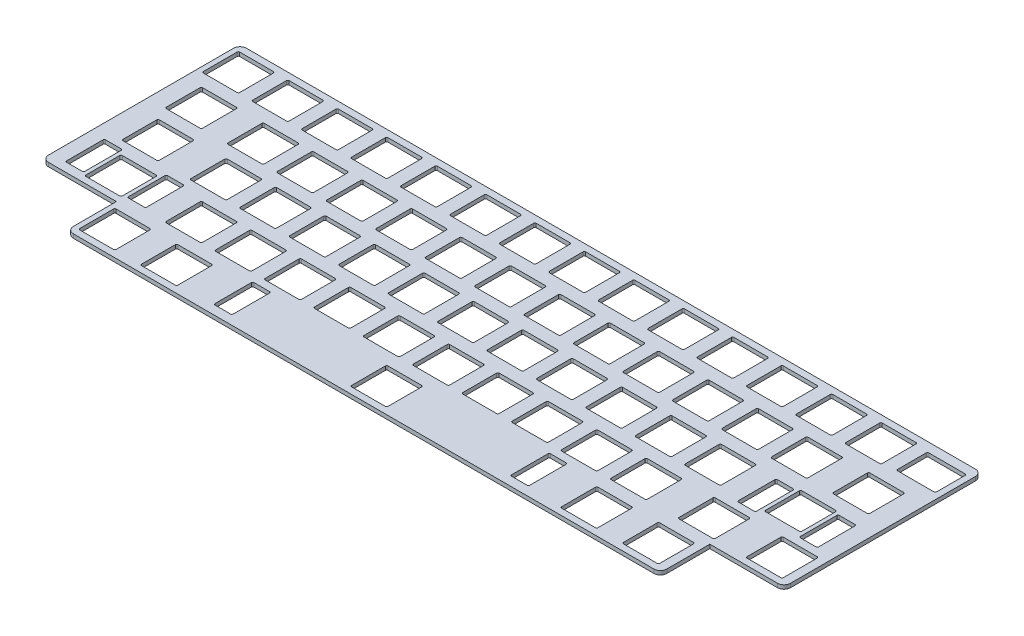
SolidWorks part; units mm, degrees
ref_plane "Front Plane" through (0, 0, 0) normal (0, 0, 1) x (1, 0, 0)
ref_plane "Top Plane" through (0, 0, 0) normal (0, 1, 0) x (1, 0, 0)
ref_plane "Right Plane" through (0, 0, 0) normal (1, 0, 0) x (0, 0, -1)
sketch "Sketch1" plane through (0, 0, 0) normal (0, 1, 0) x (1, 0, 0)
  line L0 (3.0233, -2.5236) -> (16.0159, -2.5236)
  line L1 (3.0233, -16.5156) -> (16.0159, -16.5156)
  line L2 (2.5236, -3.0233) -> (2.5236, -16.0159)
  line L3 (16.5156, -3.0233) -> (16.5156, -16.0159)
  line L4 (22.0624, -2.5236) -> (35.055, -2.5236)
  line L5 (22.0624, -16.5156) -> (35.055, -16.5156)
  line L6 (21.5627, -3.0233) -> (21.5627, -16.0159)
  line L7 (35.5547, -3.0233) -> (35.5547, -16.0159)
  line L8 (41.1015, -2.5236) -> (54.0941, -2.5236)
  line L9 (41.1015, -16.5156) -> (54.0941, -16.5156)
  line L10 (40.6018, -3.0233) -> (40.6018, -16.0159)
  line L11 (54.5938, -3.0233) -> (54.5938, -16.0159)
  line L12 (60.1407, -2.5236) -> (73.1333, -2.5236)
  line L13 (60.1407, -16.5156) -> (73.1333, -16.5156)
  line L14 (59.641, -3.0233) -> (59.641, -16.0159)
  line L15 (73.633, -3.0233) -> (73.633, -16.0159)
  line L16 (79.1798, -2.5236) -> (92.1724, -2.5236)
  line L17 (79.1798, -16.5156) -> (92.1724, -16.5156)
  line L18 (78.6801, -3.0233) -> (78.6801, -16.0159)
  line L19 (92.6721, -3.0233) -> (92.6721, -16.0159)
  line L20 (98.2189, -2.5236) -> (111.2115, -2.5236)
  line L21 (98.2189, -16.5156) -> (111.2115, -16.5156)
  line L22 (97.7192, -3.0233) -> (97.7192, -16.0159)
  line L23 (111.7112, -3.0233) -> (111.7112, -16.0159)
  line L24 (117.2581, -2.5236) -> (130.2506, -2.5236)
  line L25 (117.2581, -16.5156) -> (130.2506, -16.5156)
  line L26 (116.7584, -3.0233) -> (116.7584, -16.0159)
  line L27 (130.7504, -3.0233) -> (130.7504, -16.0159)
  line L28 (136.2972, -2.5236) -> (149.2898, -2.5236)
  line L29 (136.2972, -16.5156) -> (149.2898, -16.5156)
  line L30 (135.7975, -3.0233) -> (135.7975, -16.0159)
  line L31 (149.7895, -3.0233) -> (149.7895, -16.0159)
  line L32 (155.3363, -2.5236) -> (168.3289, -2.5236)
  line L33 (155.3363, -16.5156) -> (168.3289, -16.5156)
  line L34 (154.8366, -3.0233) -> (154.8366, -16.0159)
  line L35 (168.8286, -3.0233) -> (168.8286, -16.0159)
  line L36 (174.3755, -2.5236) -> (187.368, -2.5236)
  line L37 (174.3755, -16.5156) -> (187.368, -16.5156)
  line L38 (173.8757, -3.0233) -> (173.8757, -16.0159)
  line L39 (187.8678, -3.0233) -> (187.8678, -16.0159)
  line L40 (193.4146, -2.5236) -> (206.4072, -2.5236)
  line L41 (193.4146, -16.5156) -> (206.4072, -16.5156)
  line L42 (192.9149, -3.0233) -> (192.9149, -16.0159)
  line L43 (206.9069, -3.0233) -> (206.9069, -16.0159)
  line L44 (212.4537, -2.5236) -> (225.4463, -2.5236)
  line L45 (212.4537, -16.5156) -> (225.4463, -16.5156)
  line L46 (211.954, -3.0233) -> (211.954, -16.0159)
  line L47 (225.946, -3.0233) -> (225.946, -16.0159)
  line L48 (231.4929, -2.5236) -> (244.4854, -2.5236)
  line L49 (231.4929, -16.5156) -> (244.4854, -16.5156)
  line L50 (230.9931, -3.0233) -> (230.9931, -16.0159)
  line L51 (244.9852, -3.0233) -> (244.9852, -16.0159)
  line L52 (250.532, -2.5236) -> (263.5246, -2.5236)
  line L53 (250.532, -16.5156) -> (263.5246, -16.5156)
  line L54 (250.0323, -3.0233) -> (250.0323, -16.0159)
  line L55 (264.0243, -3.0233) -> (264.0243, -16.0159)
  line L56 (7.7831, -21.5627) -> (20.7756, -21.5627)
  line L57 (7.7831, -35.5547) -> (20.7756, -35.5547)
  line L58 (7.2833, -22.0624) -> (7.2833, -35.055)
  line L59 (21.2754, -22.0624) -> (21.2754, -35.055)
  line L60 (31.582, -21.5627) -> (44.5746, -21.5627)
  line L61 (31.582, -35.5547) -> (44.5746, -35.5547)
  line L62 (31.0823, -22.0624) -> (31.0823, -35.055)
  line L63 (45.0743, -22.0624) -> (45.0743, -35.055)
  line L64 (50.6211, -21.5627) -> (63.6137, -21.5627)
  line L65 (50.6211, -35.5547) -> (63.6137, -35.5547)
  line L66 (50.1214, -22.0624) -> (50.1214, -35.055)
  line L67 (64.1134, -22.0624) -> (64.1134, -35.055)
  line L68 (69.6602, -21.5627) -> (82.6528, -21.5627)
  line L69 (69.6602, -35.5547) -> (82.6528, -35.5547)
  line L70 (69.1605, -22.0624) -> (69.1605, -35.055)
  line L71 (83.1525, -22.0624) -> (83.1525, -35.055)
  line L72 (88.6994, -21.5627) -> (101.692, -21.5627)
  line L73 (88.6994, -35.5547) -> (101.692, -35.5547)
  line L74 (88.1997, -22.0624) -> (88.1997, -35.055)
  line L75 (102.1917, -22.0624) -> (102.1917, -35.055)
  line L76 (107.7385, -21.5627) -> (120.7311, -21.5627)
  line L77 (107.7385, -35.5547) -> (120.7311, -35.5547)
  line L78 (107.2388, -22.0624) -> (107.2388, -35.055)
  line L79 (121.2308, -22.0624) -> (121.2308, -35.055)
  line L80 (126.7776, -21.5627) -> (139.7702, -21.5627)
  line L81 (126.7776, -35.5547) -> (139.7702, -35.5547)
  line L82 (126.2779, -22.0624) -> (126.2779, -35.055)
  line L83 (140.2699, -22.0624) -> (140.2699, -35.055)
  line L84 (145.8168, -21.5627) -> (158.8093, -21.5627)
  line L85 (145.8168, -35.5547) -> (158.8093, -35.5547)
  line L86 (145.317, -22.0624) -> (145.317, -35.055)
  line L87 (159.3091, -22.0624) -> (159.3091, -35.055)
  line L88 (164.8559, -21.5627) -> (177.8485, -21.5627)
  line L89 (164.8559, -35.5547) -> (177.8485, -35.5547)
  line L90 (164.3562, -22.0624) -> (164.3562, -35.055)
  line L91 (178.3482, -22.0624) -> (178.3482, -35.055)
  line L92 (183.895, -21.5627) -> (196.8876, -21.5627)
  line L93 (183.895, -35.5547) -> (196.8876, -35.5547)
  line L94 (183.3953, -22.0624) -> (183.3953, -35.055)
  line L95 (197.3873, -22.0624) -> (197.3873, -35.055)
  line L96 (202.9342, -21.5627) -> (215.9267, -21.5627)
  line L97 (202.9342, -35.5547) -> (215.9267, -35.5547)
  line L98 (202.4344, -22.0624) -> (202.4344, -35.055)
  line L99 (216.4265, -22.0624) -> (216.4265, -35.055)
  line L100 (221.9733, -21.5627) -> (234.9659, -21.5627)
  line L101 (221.9733, -35.5547) -> (234.9659, -35.5547)
  line L102 (221.4736, -22.0624) -> (221.4736, -35.055)
  line L103 (235.4656, -22.0624) -> (235.4656, -35.055)
  line L104 (241.0124, -21.5627) -> (254.005, -21.5627)
  line L105 (241.0124, -35.5547) -> (254.005, -35.5547)
  line L106 (240.5127, -22.0624) -> (240.5127, -35.055)
  line L107 (254.5047, -22.0624) -> (254.5047, -35.055)
  line L108 (264.8113, -21.5627) -> (277.8039, -21.5627)
  line L109 (264.8113, -35.5547) -> (277.8039, -35.5547)
  line L110 (264.3116, -22.0624) -> (264.3116, -35.055)
  line L111 (278.3036, -22.0624) -> (278.3036, -35.055)
  line L112 (10.1629, -40.6018) -> (23.1555, -40.6018)
  line L113 (10.1629, -54.5938) -> (23.1555, -54.5938)
  line L114 (9.6632, -41.1015) -> (9.6632, -54.0941)
  line L115 (23.6552, -41.1015) -> (23.6552, -54.0941)
  line L116 (36.3418, -40.6018) -> (49.3343, -40.6018)
  line L117 (36.3418, -54.5938) -> (49.3343, -54.5938)
  line L118 (35.842, -41.1015) -> (35.842, -54.0941)
  line L119 (49.8341, -41.1015) -> (49.8341, -54.0941)
  line L120 (55.3809, -40.6018) -> (68.3735, -40.6018)
  line L121 (55.3809, -54.5938) -> (68.3735, -54.5938)
  line L122 (54.8812, -41.1015) -> (54.8812, -54.0941)
  line L123 (68.8732, -41.1015) -> (68.8732, -54.0941)
  line L124 (74.42, -40.6018) -> (87.4126, -40.6018)
  line L125 (74.42, -54.5938) -> (87.4126, -54.5938)
  line L126 (73.9203, -41.1015) -> (73.9203, -54.0941)
  line L127 (87.9123, -41.1015) -> (87.9123, -54.0941)
  line L128 (93.4592, -40.6018) -> (106.4517, -40.6018)
  line L129 (93.4592, -54.5938) -> (106.4517, -54.5938)
  line L130 (92.9594, -41.1015) -> (92.9594, -54.0941)
  line L131 (106.9514, -41.1015) -> (106.9514, -54.0941)
  line L132 (112.4983, -40.6018) -> (125.4909, -40.6018)
  line L133 (112.4983, -54.5938) -> (125.4909, -54.5938)
  line L134 (111.9986, -41.1015) -> (111.9986, -54.0941)
  line L135 (125.9906, -41.1015) -> (125.9906, -54.0941)
  line L136 (131.5374, -40.6018) -> (144.53, -40.6018)
  line L137 (131.5374, -54.5938) -> (144.53, -54.5938)
  line L138 (131.0377, -41.1015) -> (131.0377, -54.0941)
  line L139 (145.0297, -41.1015) -> (145.0297, -54.0941)
  line L140 (150.5765, -40.6018) -> (163.5691, -40.6018)
  line L141 (150.5765, -54.5938) -> (163.5691, -54.5938)
  line L142 (150.0768, -41.1015) -> (150.0768, -54.0941)
  line L143 (164.0688, -41.1015) -> (164.0688, -54.0941)
  line L144 (169.6157, -40.6018) -> (182.6083, -40.6018)
  line L145 (169.6157, -54.5938) -> (182.6083, -54.5938)
  line L146 (169.116, -41.1015) -> (169.116, -54.0941)
  line L147 (183.108, -41.1015) -> (183.108, -54.0941)
  line L148 (188.6548, -40.6018) -> (201.6474, -40.6018)
  line L149 (188.6548, -54.5938) -> (201.6474, -54.5938)
  line L150 (188.1551, -41.1015) -> (188.1551, -54.0941)
  line L151 (202.1471, -41.1015) -> (202.1471, -54.0941)
  line L152 (207.6939, -40.6018) -> (220.6865, -40.6018)
  line L153 (207.6939, -54.5938) -> (220.6865, -54.5938)
  line L154 (207.1942, -41.1015) -> (207.1942, -54.0941)
  line L155 (221.1862, -41.1015) -> (221.1862, -54.0941)
  line L156 (226.7331, -40.6018) -> (239.7257, -40.6018)
  line L157 (226.7331, -54.5938) -> (239.7257, -54.5938)
  line L158 (226.2334, -41.1015) -> (226.2334, -54.0941)
  line L159 (240.2254, -41.1015) -> (240.2254, -54.0941)
  line L160 (257.6717, -40.6018) -> (270.6642, -40.6018)
  line L161 (257.6717, -54.5938) -> (270.6642, -54.5938)
  line L162 (257.172, -41.1015) -> (257.172, -54.0941)
  line L163 (271.164, -41.1015) -> (271.164, -54.0941)
  line L164 (249.2385, -41.6013) -> (255.2351, -41.6013)
  line L165 (249.2385, -56.5927) -> (255.2351, -56.5927)
  line L166 (248.7388, -42.101) -> (248.7388, -56.093)
  line L167 (255.7348, -42.101) -> (255.7348, -56.093)
  line L168 (273.1009, -41.6013) -> (279.0974, -41.6013)
  line L169 (273.1009, -56.5927) -> (279.0974, -56.5927)
  line L170 (272.6011, -42.101) -> (272.6011, -56.093)
  line L171 (279.5971, -42.101) -> (279.5971, -56.093)
  line L172 (45.8613, -59.641) -> (58.8539, -59.641)
  line L173 (45.8613, -73.633) -> (58.8539, -73.633)
  line L174 (45.3616, -60.1407) -> (45.3616, -73.1333)
  line L175 (59.3536, -60.1407) -> (59.3536, -73.1333)
  line L176 (64.9005, -59.641) -> (77.893, -59.641)
  line L177 (64.9005, -73.633) -> (77.893, -73.633)
  line L178 (64.4007, -60.1407) -> (64.4007, -73.1333)
  line L179 (78.3928, -60.1407) -> (78.3928, -73.1333)
  line L180 (83.9396, -59.641) -> (96.9322, -59.641)
  line L181 (83.9396, -73.633) -> (96.9322, -73.633)
  line L182 (83.4399, -60.1407) -> (83.4399, -73.1333)
  line L183 (97.4319, -60.1407) -> (97.4319, -73.1333)
  line L184 (102.9787, -59.641) -> (115.9713, -59.641)
  line L185 (102.9787, -73.633) -> (115.9713, -73.633)
  line L186 (102.479, -60.1407) -> (102.479, -73.1333)
  line L187 (116.471, -60.1407) -> (116.471, -73.1333)
  line L188 (122.0178, -59.641) -> (135.0104, -59.641)
  line L189 (122.0178, -73.633) -> (135.0104, -73.633)
  line L190 (121.5181, -60.1407) -> (121.5181, -73.1333)
  line L191 (135.5101, -60.1407) -> (135.5101, -73.1333)
  line L192 (141.057, -59.641) -> (154.0496, -59.641)
  line L193 (141.057, -73.633) -> (154.0496, -73.633)
  line L194 (140.5573, -60.1407) -> (140.5573, -73.1333)
  line L195 (154.5493, -60.1407) -> (154.5493, -73.1333)
  line L196 (160.0961, -59.641) -> (173.0887, -59.641)
  line L197 (160.0961, -73.633) -> (173.0887, -73.633)
  line L198 (159.5964, -60.1407) -> (159.5964, -73.1333)
  line L199 (173.5884, -60.1407) -> (173.5884, -73.1333)
  line L200 (179.1352, -59.641) -> (192.1278, -59.641)
  line L201 (179.1352, -73.633) -> (192.1278, -73.633)
  line L202 (178.6355, -60.1407) -> (178.6355, -73.1333)
  line L203 (192.6275, -60.1407) -> (192.6275, -73.1333)
  line L204 (198.1744, -59.641) -> (211.167, -59.641)
  line L205 (198.1744, -73.633) -> (211.167, -73.633)
  line L206 (197.6747, -60.1407) -> (197.6747, -73.1333)
  line L207 (211.6667, -60.1407) -> (211.6667, -73.1333)
  line L208 (217.2135, -59.641) -> (230.2061, -59.641)
  line L209 (217.2135, -73.633) -> (230.2061, -73.633)
  line L210 (216.7138, -60.1407) -> (216.7138, -73.1333)
  line L211 (230.7058, -60.1407) -> (230.7058, -73.1333)
  line L212 (243.3923, -59.641) -> (256.3849, -59.641)
  line L213 (243.3923, -73.633) -> (256.3849, -73.633)
  line L214 (242.8926, -60.1407) -> (242.8926, -73.1333)
  line L215 (256.8846, -60.1407) -> (256.8846, -73.1333)
  line L216 (269.5711, -59.641) -> (282.5637, -59.641)
  line L217 (269.5711, -73.633) -> (282.5637, -73.633)
  line L218 (269.0714, -60.1407) -> (269.0714, -73.1333)
  line L219 (283.0634, -60.1407) -> (283.0634, -73.1333)
  line L220 (31.582, -78.6801) -> (44.5746, -78.6801)
  line L221 (31.582, -92.6721) -> (44.5746, -92.6721)
  line L222 (31.0823, -79.1798) -> (31.0823, -92.1724)
  line L223 (45.0743, -79.1798) -> (45.0743, -92.1724)
  line L224 (55.3809, -78.6801) -> (68.3735, -78.6801)
  line L225 (55.3809, -92.6721) -> (68.3735, -92.6721)
  line L226 (54.8812, -79.1798) -> (54.8812, -92.1724)
  line L227 (68.8732, -79.1798) -> (68.8732, -92.1724)
  line L228 (217.2135, -78.6801) -> (230.2061, -78.6801)
  line L229 (217.2135, -92.6721) -> (230.2061, -92.6721)
  line L230 (216.7138, -79.1798) -> (216.7138, -92.1724)
  line L231 (230.7058, -79.1798) -> (230.7058, -92.1724)
  line L232 (241.0124, -78.6801) -> (254.005, -78.6801)
  line L233 (241.0124, -92.6721) -> (254.005, -92.6721)
  line L234 (240.5127, -79.1798) -> (240.5127, -92.1724)
  line L235 (254.5047, -79.1798) -> (254.5047, -92.1724)
  line L236 (27.9153, -73.633) -> (14.9227, -73.633)
  line L237 (27.9153, -59.641) -> (14.9227, -59.641)
  line L238 (28.415, -73.1333) -> (28.415, -60.1407)
  line L239 (14.423, -73.1333) -> (14.423, -60.1407)
  line L240 (36.3485, -72.6335) -> (30.3519, -72.6335)
  line L241 (36.3485, -57.6421) -> (30.3519, -57.6421)
  line L242 (36.8482, -72.1338) -> (36.8482, -58.1418)
  line L243 (29.8522, -72.1338) -> (29.8522, -58.1418)
  line L244 (12.4861, -72.6335) -> (6.4895, -72.6335)
  line L245 (12.4861, -57.6421) -> (6.4895, -57.6421)
  line L246 (12.9858, -72.1338) -> (12.9858, -58.1418)
  line L247 (5.9898, -72.1338) -> (5.9898, -58.1418)
  line L248 (149.2898, -92.6721) -> (136.2972, -92.6721)
  line L249 (149.2898, -78.6801) -> (136.2972, -78.6801)
  line L250 (149.7895, -92.1724) -> (149.7895, -79.1798)
  line L251 (135.7975, -92.1724) -> (135.7975, -79.1798)
  line L252 (202.9092, -91.6727) -> (196.9126, -91.6727)
  line L253 (202.9092, -76.6812) -> (196.9126, -76.6812)
  line L254 (203.4089, -91.173) -> (203.4089, -77.1809)
  line L255 (196.4129, -91.173) -> (196.4129, -77.1809)
  line L256 (88.6744, -91.6727) -> (82.6778, -91.6727)
  line L257 (88.6744, -76.6812) -> (82.6778, -76.6812)
  line L258 (89.1741, -91.173) -> (89.1741, -77.1809)
  line L259 (82.1781, -91.173) -> (82.1781, -77.1809)
  line L260 (0.5696, -95.1957) -> (286.3196, -95.1957) construction
  line L261 (0.5696, 0.0543) -> (286.3196, 0.0543)
  line L262 (0.5696, -95.1957) -> (0.5696, 0.0543) construction
  line L263 (286.3196, -95.1957) -> (286.3196, 0.0543) construction
  line L264 (29.1446, -95.1957) -> (29.1446, -76.1457)
  line L265 (29.1446, -76.1457) -> (0.5696, -76.1457)
  line L266 (0.5696, 0.0543) -> (0.5696, -76.1457)
  line L267 (286.3196, -76.1457) -> (257.7446, -76.1457)
  line L268 (257.7446, -76.1457) -> (257.7446, -95.1957)
  line L269 (29.1446, -95.1957) -> (257.7446, -95.1957)
  line L270 (286.3196, 0.0543) -> (286.3196, -76.1457)
  line L271 (264.0243, -9.5196) -> (266.6022, -9.5196) construction
  line L272 (266.6022, -9.5196) -> (286.3196, -9.5196) construction
  line L279 (257.0283, -2.5236) -> (257.0283, 0.0543) construction
  line L280 (276.4609, -15.5196) -> (276.4609, -3.5196) construction
  line L281 (283.4609, -3.5196) -> (269.4609, -3.5196)
  line L282 (268.9609, -4.0196) -> (268.9609, -15.0196)
  line L283 (269.4609, -15.5196) -> (283.4609, -15.5196)
  line L284 (283.9609, -15.0196) -> (283.9609, -4.0196)
  arc A0 (3.0233, -2.5236) -> (2.5236, -3.0233) centre (3.0233, -3.0233) ccw
  arc A1 (16.5156, -3.0233) -> (16.0159, -2.5236) centre (16.0159, -3.0233) ccw
  arc A2 (2.5236, -16.0159) -> (3.0233, -16.5156) centre (3.0233, -16.0159) ccw
  arc A3 (16.0159, -16.5156) -> (16.5156, -16.0159) centre (16.0159, -16.0159) ccw
  arc A4 (22.0624, -2.5236) -> (21.5627, -3.0233) centre (22.0624, -3.0233) ccw
  arc A5 (35.5547, -3.0233) -> (35.055, -2.5236) centre (35.055, -3.0233) ccw
  arc A6 (21.5627, -16.0159) -> (22.0624, -16.5156) centre (22.0624, -16.0159) ccw
  arc A7 (35.055, -16.5156) -> (35.5547, -16.0159) centre (35.055, -16.0159) ccw
  arc A8 (41.1015, -2.5236) -> (40.6018, -3.0233) centre (41.1015, -3.0233) ccw
  arc A9 (54.5938, -3.0233) -> (54.0941, -2.5236) centre (54.0941, -3.0233) ccw
  arc A10 (40.6018, -16.0159) -> (41.1015, -16.5156) centre (41.1015, -16.0159) ccw
  arc A11 (54.0941, -16.5156) -> (54.5938, -16.0159) centre (54.0941, -16.0159) ccw
  arc A12 (60.1407, -2.5236) -> (59.641, -3.0233) centre (60.1407, -3.0233) ccw
  arc A13 (73.633, -3.0233) -> (73.1333, -2.5236) centre (73.1333, -3.0233) ccw
  arc A14 (59.641, -16.0159) -> (60.1407, -16.5156) centre (60.1407, -16.0159) ccw
  arc A15 (73.1333, -16.5156) -> (73.633, -16.0159) centre (73.1333, -16.0159) ccw
  arc A16 (79.1798, -2.5236) -> (78.6801, -3.0233) centre (79.1798, -3.0233) ccw
  arc A17 (92.6721, -3.0233) -> (92.1724, -2.5236) centre (92.1724, -3.0233) ccw
  arc A18 (78.6801, -16.0159) -> (79.1798, -16.5156) centre (79.1798, -16.0159) ccw
  arc A19 (92.1724, -16.5156) -> (92.6721, -16.0159) centre (92.1724, -16.0159) ccw
  arc A20 (98.2189, -2.5236) -> (97.7192, -3.0233) centre (98.2189, -3.0233) ccw
  arc A21 (111.7112, -3.0233) -> (111.2115, -2.5236) centre (111.2115, -3.0233) ccw
  arc A22 (97.7192, -16.0159) -> (98.2189, -16.5156) centre (98.2189, -16.0159) ccw
  arc A23 (111.2115, -16.5156) -> (111.7112, -16.0159) centre (111.2115, -16.0159) ccw
  arc A24 (117.2581, -2.5236) -> (116.7584, -3.0233) centre (117.2581, -3.0233) ccw
  arc A25 (130.7504, -3.0233) -> (130.2506, -2.5236) centre (130.2506, -3.0233) ccw
  arc A26 (116.7584, -16.0159) -> (117.2581, -16.5156) centre (117.2581, -16.0159) ccw
  arc A27 (130.2506, -16.5156) -> (130.7504, -16.0159) centre (130.2506, -16.0159) ccw
  arc A28 (136.2972, -2.5236) -> (135.7975, -3.0233) centre (136.2972, -3.0233) ccw
  arc A29 (149.7895, -3.0233) -> (149.2898, -2.5236) centre (149.2898, -3.0233) ccw
  arc A30 (135.7975, -16.0159) -> (136.2972, -16.5156) centre (136.2972, -16.0159) ccw
  arc A31 (149.2898, -16.5156) -> (149.7895, -16.0159) centre (149.2898, -16.0159) ccw
  arc A32 (155.3363, -2.5236) -> (154.8366, -3.0233) centre (155.3363, -3.0233) ccw
  arc A33 (168.8286, -3.0233) -> (168.3289, -2.5236) centre (168.3289, -3.0233) ccw
  arc A34 (154.8366, -16.0159) -> (155.3363, -16.5156) centre (155.3363, -16.0159) ccw
  arc A35 (168.3289, -16.5156) -> (168.8286, -16.0159) centre (168.3289, -16.0159) ccw
  arc A36 (174.3755, -2.5236) -> (173.8757, -3.0233) centre (174.3755, -3.0233) ccw
  arc A37 (187.8678, -3.0233) -> (187.368, -2.5236) centre (187.368, -3.0233) ccw
  arc A38 (173.8757, -16.0159) -> (174.3755, -16.5156) centre (174.3755, -16.0159) ccw
  arc A39 (187.368, -16.5156) -> (187.8678, -16.0159) centre (187.368, -16.0159) ccw
  arc A40 (193.4146, -2.5236) -> (192.9149, -3.0233) centre (193.4146, -3.0233) ccw
  arc A41 (206.9069, -3.0233) -> (206.4072, -2.5236) centre (206.4072, -3.0233) ccw
  arc A42 (192.9149, -16.0159) -> (193.4146, -16.5156) centre (193.4146, -16.0159) ccw
  arc A43 (206.4072, -16.5156) -> (206.9069, -16.0159) centre (206.4072, -16.0159) ccw
  arc A44 (212.4537, -2.5236) -> (211.954, -3.0233) centre (212.4537, -3.0233) ccw
  arc A45 (225.946, -3.0233) -> (225.4463, -2.5236) centre (225.4463, -3.0233) ccw
  arc A46 (211.954, -16.0159) -> (212.4537, -16.5156) centre (212.4537, -16.0159) ccw
  arc A47 (225.4463, -16.5156) -> (225.946, -16.0159) centre (225.4463, -16.0159) ccw
  arc A48 (231.4929, -2.5236) -> (230.9931, -3.0233) centre (231.4929, -3.0233) ccw
  arc A49 (244.9852, -3.0233) -> (244.4854, -2.5236) centre (244.4854, -3.0233) ccw
  arc A50 (230.9931, -16.0159) -> (231.4929, -16.5156) centre (231.4929, -16.0159) ccw
  arc A51 (244.4854, -16.5156) -> (244.9852, -16.0159) centre (244.4854, -16.0159) ccw
  arc A52 (250.532, -2.5236) -> (250.0323, -3.0233) centre (250.532, -3.0233) ccw
  arc A53 (264.0243, -3.0233) -> (263.5246, -2.5236) centre (263.5246, -3.0233) ccw
  arc A54 (250.0323, -16.0159) -> (250.532, -16.5156) centre (250.532, -16.0159) ccw
  arc A55 (263.5246, -16.5156) -> (264.0243, -16.0159) centre (263.5246, -16.0159) ccw
  arc A56 (7.7831, -21.5627) -> (7.2833, -22.0624) centre (7.7831, -22.0624) ccw
  arc A57 (21.2754, -22.0624) -> (20.7756, -21.5627) centre (20.7756, -22.0624) ccw
  arc A58 (7.2833, -35.055) -> (7.7831, -35.5547) centre (7.7831, -35.055) ccw
  arc A59 (20.7756, -35.5547) -> (21.2754, -35.055) centre (20.7756, -35.055) ccw
  arc A60 (31.582, -21.5627) -> (31.0823, -22.0624) centre (31.582, -22.0624) ccw
  arc A61 (45.0743, -22.0624) -> (44.5746, -21.5627) centre (44.5746, -22.0624) ccw
  arc A62 (31.0823, -35.055) -> (31.582, -35.5547) centre (31.582, -35.055) ccw
  arc A63 (44.5746, -35.5547) -> (45.0743, -35.055) centre (44.5746, -35.055) ccw
  arc A64 (50.6211, -21.5627) -> (50.1214, -22.0624) centre (50.6211, -22.0624) ccw
  arc A65 (64.1134, -22.0624) -> (63.6137, -21.5627) centre (63.6137, -22.0624) ccw
  arc A66 (50.1214, -35.055) -> (50.6211, -35.5547) centre (50.6211, -35.055) ccw
  arc A67 (63.6137, -35.5547) -> (64.1134, -35.055) centre (63.6137, -35.055) ccw
  arc A68 (69.6602, -21.5627) -> (69.1605, -22.0624) centre (69.6602, -22.0624) ccw
  arc A69 (83.1525, -22.0624) -> (82.6528, -21.5627) centre (82.6528, -22.0624) ccw
  arc A70 (69.1605, -35.055) -> (69.6602, -35.5547) centre (69.6602, -35.055) ccw
  arc A71 (82.6528, -35.5547) -> (83.1525, -35.055) centre (82.6528, -35.055) ccw
  arc A72 (88.6994, -21.5627) -> (88.1997, -22.0624) centre (88.6994, -22.0624) ccw
  arc A73 (102.1917, -22.0624) -> (101.692, -21.5627) centre (101.692, -22.0624) ccw
  arc A74 (88.1997, -35.055) -> (88.6994, -35.5547) centre (88.6994, -35.055) ccw
  arc A75 (101.692, -35.5547) -> (102.1917, -35.055) centre (101.692, -35.055) ccw
  arc A76 (107.7385, -21.5627) -> (107.2388, -22.0624) centre (107.7385, -22.0624) ccw
  arc A77 (121.2308, -22.0624) -> (120.7311, -21.5627) centre (120.7311, -22.0624) ccw
  arc A78 (107.2388, -35.055) -> (107.7385, -35.5547) centre (107.7385, -35.055) ccw
  arc A79 (120.7311, -35.5547) -> (121.2308, -35.055) centre (120.7311, -35.055) ccw
  arc A80 (126.7776, -21.5627) -> (126.2779, -22.0624) centre (126.7776, -22.0624) ccw
  arc A81 (140.2699, -22.0624) -> (139.7702, -21.5627) centre (139.7702, -22.0624) ccw
  arc A82 (126.2779, -35.055) -> (126.7776, -35.5547) centre (126.7776, -35.055) ccw
  arc A83 (139.7702, -35.5547) -> (140.2699, -35.055) centre (139.7702, -35.055) ccw
  arc A84 (145.8168, -21.5627) -> (145.317, -22.0624) centre (145.8168, -22.0624) ccw
  arc A85 (159.3091, -22.0624) -> (158.8093, -21.5627) centre (158.8093, -22.0624) ccw
  arc A86 (145.317, -35.055) -> (145.8168, -35.5547) centre (145.8168, -35.055) ccw
  arc A87 (158.8093, -35.5547) -> (159.3091, -35.055) centre (158.8093, -35.055) ccw
  arc A88 (164.8559, -21.5627) -> (164.3562, -22.0624) centre (164.8559, -22.0624) ccw
  arc A89 (178.3482, -22.0624) -> (177.8485, -21.5627) centre (177.8485, -22.0624) ccw
  arc A90 (164.3562, -35.055) -> (164.8559, -35.5547) centre (164.8559, -35.055) ccw
  arc A91 (177.8485, -35.5547) -> (178.3482, -35.055) centre (177.8485, -35.055) ccw
  arc A92 (183.895, -21.5627) -> (183.3953, -22.0624) centre (183.895, -22.0624) ccw
  arc A93 (197.3873, -22.0624) -> (196.8876, -21.5627) centre (196.8876, -22.0624) ccw
  arc A94 (183.3953, -35.055) -> (183.895, -35.5547) centre (183.895, -35.055) ccw
  arc A95 (196.8876, -35.5547) -> (197.3873, -35.055) centre (196.8876, -35.055) ccw
  arc A96 (202.9342, -21.5627) -> (202.4344, -22.0624) centre (202.9342, -22.0624) ccw
  arc A97 (216.4265, -22.0624) -> (215.9267, -21.5627) centre (215.9267, -22.0624) ccw
  arc A98 (202.4344, -35.055) -> (202.9342, -35.5547) centre (202.9342, -35.055) ccw
  arc A99 (215.9267, -35.5547) -> (216.4265, -35.055) centre (215.9267, -35.055) ccw
  arc A100 (221.9733, -21.5627) -> (221.4736, -22.0624) centre (221.9733, -22.0624) ccw
  arc A101 (235.4656, -22.0624) -> (234.9659, -21.5627) centre (234.9659, -22.0624) ccw
  arc A102 (221.4736, -35.055) -> (221.9733, -35.5547) centre (221.9733, -35.055) ccw
  arc A103 (234.9659, -35.5547) -> (235.4656, -35.055) centre (234.9659, -35.055) ccw
  arc A104 (241.0124, -21.5627) -> (240.5127, -22.0624) centre (241.0124, -22.0624) ccw
  arc A105 (254.5047, -22.0624) -> (254.005, -21.5627) centre (254.005, -22.0624) ccw
  arc A106 (240.5127, -35.055) -> (241.0124, -35.5547) centre (241.0124, -35.055) ccw
  arc A107 (254.005, -35.5547) -> (254.5047, -35.055) centre (254.005, -35.055) ccw
  arc A108 (264.8113, -21.5627) -> (264.3116, -22.0624) centre (264.8113, -22.0624) ccw
  arc A109 (278.3036, -22.0624) -> (277.8039, -21.5627) centre (277.8039, -22.0624) ccw
  arc A110 (264.3116, -35.055) -> (264.8113, -35.5547) centre (264.8113, -35.055) ccw
  arc A111 (277.8039, -35.5547) -> (278.3036, -35.055) centre (277.8039, -35.055) ccw
  arc A112 (10.1629, -40.6018) -> (9.6632, -41.1015) centre (10.1629, -41.1015) ccw
  arc A113 (23.6552, -41.1015) -> (23.1555, -40.6018) centre (23.1555, -41.1015) ccw
  arc A114 (9.6632, -54.0941) -> (10.1629, -54.5938) centre (10.1629, -54.0941) ccw
  arc A115 (23.1555, -54.5938) -> (23.6552, -54.0941) centre (23.1555, -54.0941) ccw
  arc A116 (36.3418, -40.6018) -> (35.842, -41.1015) centre (36.3418, -41.1015) ccw
  arc A117 (49.8341, -41.1015) -> (49.3343, -40.6018) centre (49.3343, -41.1015) ccw
  arc A118 (35.842, -54.0941) -> (36.3418, -54.5938) centre (36.3418, -54.0941) ccw
  arc A119 (49.3343, -54.5938) -> (49.8341, -54.0941) centre (49.3343, -54.0941) ccw
  arc A120 (55.3809, -40.6018) -> (54.8812, -41.1015) centre (55.3809, -41.1015) ccw
  arc A121 (68.8732, -41.1015) -> (68.3735, -40.6018) centre (68.3735, -41.1015) ccw
  arc A122 (54.8812, -54.0941) -> (55.3809, -54.5938) centre (55.3809, -54.0941) ccw
  arc A123 (68.3735, -54.5938) -> (68.8732, -54.0941) centre (68.3735, -54.0941) ccw
  arc A124 (74.42, -40.6018) -> (73.9203, -41.1015) centre (74.42, -41.1015) ccw
  arc A125 (87.9123, -41.1015) -> (87.4126, -40.6018) centre (87.4126, -41.1015) ccw
  arc A126 (73.9203, -54.0941) -> (74.42, -54.5938) centre (74.42, -54.0941) ccw
  arc A127 (87.4126, -54.5938) -> (87.9123, -54.0941) centre (87.4126, -54.0941) ccw
  arc A128 (93.4592, -40.6018) -> (92.9594, -41.1015) centre (93.4592, -41.1015) ccw
  arc A129 (106.9514, -41.1015) -> (106.4517, -40.6018) centre (106.4517, -41.1015) ccw
  arc A130 (92.9594, -54.0941) -> (93.4592, -54.5938) centre (93.4592, -54.0941) ccw
  arc A131 (106.4517, -54.5938) -> (106.9514, -54.0941) centre (106.4517, -54.0941) ccw
  arc A132 (112.4983, -40.6018) -> (111.9986, -41.1015) centre (112.4983, -41.1015) ccw
  arc A133 (125.9906, -41.1015) -> (125.4909, -40.6018) centre (125.4909, -41.1015) ccw
  arc A134 (111.9986, -54.0941) -> (112.4983, -54.5938) centre (112.4983, -54.0941) ccw
  arc A135 (125.4909, -54.5938) -> (125.9906, -54.0941) centre (125.4909, -54.0941) ccw
  arc A136 (131.5374, -40.6018) -> (131.0377, -41.1015) centre (131.5374, -41.1015) ccw
  arc A137 (145.0297, -41.1015) -> (144.53, -40.6018) centre (144.53, -41.1015) ccw
  arc A138 (131.0377, -54.0941) -> (131.5374, -54.5938) centre (131.5374, -54.0941) ccw
  arc A139 (144.53, -54.5938) -> (145.0297, -54.0941) centre (144.53, -54.0941) ccw
  arc A140 (150.5765, -40.6018) -> (150.0768, -41.1015) centre (150.5765, -41.1015) ccw
  arc A141 (164.0688, -41.1015) -> (163.5691, -40.6018) centre (163.5691, -41.1015) ccw
  arc A142 (150.0768, -54.0941) -> (150.5765, -54.5938) centre (150.5765, -54.0941) ccw
  arc A143 (163.5691, -54.5938) -> (164.0688, -54.0941) centre (163.5691, -54.0941) ccw
  arc A144 (169.6157, -40.6018) -> (169.116, -41.1015) centre (169.6157, -41.1015) ccw
  arc A145 (183.108, -41.1015) -> (182.6083, -40.6018) centre (182.6083, -41.1015) ccw
  arc A146 (169.116, -54.0941) -> (169.6157, -54.5938) centre (169.6157, -54.0941) ccw
  arc A147 (182.6083, -54.5938) -> (183.108, -54.0941) centre (182.6083, -54.0941) ccw
  arc A148 (188.6548, -40.6018) -> (188.1551, -41.1015) centre (188.6548, -41.1015) ccw
  arc A149 (202.1471, -41.1015) -> (201.6474, -40.6018) centre (201.6474, -41.1015) ccw
  arc A150 (188.1551, -54.0941) -> (188.6548, -54.5938) centre (188.6548, -54.0941) ccw
  arc A151 (201.6474, -54.5938) -> (202.1471, -54.0941) centre (201.6474, -54.0941) ccw
  arc A152 (207.6939, -40.6018) -> (207.1942, -41.1015) centre (207.6939, -41.1015) ccw
  arc A153 (221.1862, -41.1015) -> (220.6865, -40.6018) centre (220.6865, -41.1015) ccw
  arc A154 (207.1942, -54.0941) -> (207.6939, -54.5938) centre (207.6939, -54.0941) ccw
  arc A155 (220.6865, -54.5938) -> (221.1862, -54.0941) centre (220.6865, -54.0941) ccw
  arc A156 (226.7331, -40.6018) -> (226.2334, -41.1015) centre (226.7331, -41.1015) ccw
  arc A157 (240.2254, -41.1015) -> (239.7257, -40.6018) centre (239.7257, -41.1015) ccw
  arc A158 (226.2334, -54.0941) -> (226.7331, -54.5938) centre (226.7331, -54.0941) ccw
  arc A159 (239.7257, -54.5938) -> (240.2254, -54.0941) centre (239.7257, -54.0941) ccw
  arc A160 (257.6717, -40.6018) -> (257.172, -41.1015) centre (257.6717, -41.1015) ccw
  arc A161 (271.164, -41.1015) -> (270.6642, -40.6018) centre (270.6642, -41.1015) ccw
  arc A162 (257.172, -54.0941) -> (257.6717, -54.5938) centre (257.6717, -54.0941) ccw
  arc A163 (270.6642, -54.5938) -> (271.164, -54.0941) centre (270.6642, -54.0941) ccw
  arc A164 (249.2385, -41.6013) -> (248.7388, -42.101) centre (249.2385, -42.101) ccw
  arc A165 (255.7348, -42.101) -> (255.2351, -41.6013) centre (255.2351, -42.101) ccw
  arc A166 (248.7388, -56.093) -> (249.2385, -56.5927) centre (249.2385, -56.093) ccw
  arc A167 (255.2351, -56.5927) -> (255.7348, -56.093) centre (255.2351, -56.093) ccw
  arc A168 (273.1009, -41.6013) -> (272.6011, -42.101) centre (273.1009, -42.101) ccw
  arc A169 (279.5971, -42.101) -> (279.0974, -41.6013) centre (279.0974, -42.101) ccw
  arc A170 (272.6011, -56.093) -> (273.1009, -56.5927) centre (273.1009, -56.093) ccw
  arc A171 (279.0974, -56.5927) -> (279.5971, -56.093) centre (279.0974, -56.093) ccw
  arc A172 (45.8613, -59.641) -> (45.3616, -60.1407) centre (45.8613, -60.1407) ccw
  arc A173 (59.3536, -60.1407) -> (58.8539, -59.641) centre (58.8539, -60.1407) ccw
  arc A174 (45.3616, -73.1333) -> (45.8613, -73.633) centre (45.8613, -73.1333) ccw
  arc A175 (58.8539, -73.633) -> (59.3536, -73.1333) centre (58.8539, -73.1333) ccw
  arc A176 (64.9005, -59.641) -> (64.4007, -60.1407) centre (64.9005, -60.1407) ccw
  arc A177 (78.3928, -60.1407) -> (77.893, -59.641) centre (77.893, -60.1407) ccw
  arc A178 (64.4007, -73.1333) -> (64.9005, -73.633) centre (64.9005, -73.1333) ccw
  arc A179 (77.893, -73.633) -> (78.3928, -73.1333) centre (77.893, -73.1333) ccw
  arc A180 (83.9396, -59.641) -> (83.4399, -60.1407) centre (83.9396, -60.1407) ccw
  arc A181 (97.4319, -60.1407) -> (96.9322, -59.641) centre (96.9322, -60.1407) ccw
  arc A182 (83.4399, -73.1333) -> (83.9396, -73.633) centre (83.9396, -73.1333) ccw
  arc A183 (96.9322, -73.633) -> (97.4319, -73.1333) centre (96.9322, -73.1333) ccw
  arc A184 (102.9787, -59.641) -> (102.479, -60.1407) centre (102.9787, -60.1407) ccw
  arc A185 (116.471, -60.1407) -> (115.9713, -59.641) centre (115.9713, -60.1407) ccw
  arc A186 (102.479, -73.1333) -> (102.9787, -73.633) centre (102.9787, -73.1333) ccw
  arc A187 (115.9713, -73.633) -> (116.471, -73.1333) centre (115.9713, -73.1333) ccw
  arc A188 (122.0178, -59.641) -> (121.5181, -60.1407) centre (122.0178, -60.1407) ccw
  arc A189 (135.5101, -60.1407) -> (135.0104, -59.641) centre (135.0104, -60.1407) ccw
  arc A190 (121.5181, -73.1333) -> (122.0178, -73.633) centre (122.0178, -73.1333) ccw
  arc A191 (135.0104, -73.633) -> (135.5101, -73.1333) centre (135.0104, -73.1333) ccw
  arc A192 (141.057, -59.641) -> (140.5573, -60.1407) centre (141.057, -60.1407) ccw
  arc A193 (154.5493, -60.1407) -> (154.0496, -59.641) centre (154.0496, -60.1407) ccw
  arc A194 (140.5573, -73.1333) -> (141.057, -73.633) centre (141.057, -73.1333) ccw
  arc A195 (154.0496, -73.633) -> (154.5493, -73.1333) centre (154.0496, -73.1333) ccw
  arc A196 (160.0961, -59.641) -> (159.5964, -60.1407) centre (160.0961, -60.1407) ccw
  arc A197 (173.5884, -60.1407) -> (173.0887, -59.641) centre (173.0887, -60.1407) ccw
  arc A198 (159.5964, -73.1333) -> (160.0961, -73.633) centre (160.0961, -73.1333) ccw
  arc A199 (173.0887, -73.633) -> (173.5884, -73.1333) centre (173.0887, -73.1333) ccw
  arc A200 (179.1352, -59.641) -> (178.6355, -60.1407) centre (179.1352, -60.1407) ccw
  arc A201 (192.6275, -60.1407) -> (192.1278, -59.641) centre (192.1278, -60.1407) ccw
  arc A202 (178.6355, -73.1333) -> (179.1352, -73.633) centre (179.1352, -73.1333) ccw
  arc A203 (192.1278, -73.633) -> (192.6275, -73.1333) centre (192.1278, -73.1333) ccw
  arc A204 (198.1744, -59.641) -> (197.6747, -60.1407) centre (198.1744, -60.1407) ccw
  arc A205 (211.6667, -60.1407) -> (211.167, -59.641) centre (211.167, -60.1407) ccw
  arc A206 (197.6747, -73.1333) -> (198.1744, -73.633) centre (198.1744, -73.1333) ccw
  arc A207 (211.167, -73.633) -> (211.6667, -73.1333) centre (211.167, -73.1333) ccw
  arc A208 (217.2135, -59.641) -> (216.7138, -60.1407) centre (217.2135, -60.1407) ccw
  arc A209 (230.7058, -60.1407) -> (230.2061, -59.641) centre (230.2061, -60.1407) ccw
  arc A210 (216.7138, -73.1333) -> (217.2135, -73.633) centre (217.2135, -73.1333) ccw
  arc A211 (230.2061, -73.633) -> (230.7058, -73.1333) centre (230.2061, -73.1333) ccw
  arc A212 (243.3923, -59.641) -> (242.8926, -60.1407) centre (243.3923, -60.1407) ccw
  arc A213 (256.8846, -60.1407) -> (256.3849, -59.641) centre (256.3849, -60.1407) ccw
  arc A214 (242.8926, -73.1333) -> (243.3923, -73.633) centre (243.3923, -73.1333) ccw
  arc A215 (256.3849, -73.633) -> (256.8846, -73.1333) centre (256.3849, -73.1333) ccw
  arc A216 (269.5711, -59.641) -> (269.0714, -60.1407) centre (269.5711, -60.1407) ccw
  arc A217 (283.0634, -60.1407) -> (282.5637, -59.641) centre (282.5637, -60.1407) ccw
  arc A218 (269.0714, -73.1333) -> (269.5711, -73.633) centre (269.5711, -73.1333) ccw
  arc A219 (282.5637, -73.633) -> (283.0634, -73.1333) centre (282.5637, -73.1333) ccw
  arc A220 (31.582, -78.6801) -> (31.0823, -79.1798) centre (31.582, -79.1798) ccw
  arc A221 (45.0743, -79.1798) -> (44.5746, -78.6801) centre (44.5746, -79.1798) ccw
  arc A222 (31.0823, -92.1724) -> (31.582, -92.6721) centre (31.582, -92.1724) ccw
  arc A223 (44.5746, -92.6721) -> (45.0743, -92.1724) centre (44.5746, -92.1724) ccw
  arc A224 (55.3809, -78.6801) -> (54.8812, -79.1798) centre (55.3809, -79.1798) ccw
  arc A225 (68.8732, -79.1798) -> (68.3735, -78.6801) centre (68.3735, -79.1798) ccw
  arc A226 (54.8812, -92.1724) -> (55.3809, -92.6721) centre (55.3809, -92.1724) ccw
  arc A227 (68.3735, -92.6721) -> (68.8732, -92.1724) centre (68.3735, -92.1724) ccw
  arc A228 (217.2135, -78.6801) -> (216.7138, -79.1798) centre (217.2135, -79.1798) ccw
  arc A229 (230.7058, -79.1798) -> (230.2061, -78.6801) centre (230.2061, -79.1798) ccw
  arc A230 (216.7138, -92.1724) -> (217.2135, -92.6721) centre (217.2135, -92.1724) ccw
  arc A231 (230.2061, -92.6721) -> (230.7058, -92.1724) centre (230.2061, -92.1724) ccw
  arc A232 (241.0124, -78.6801) -> (240.5127, -79.1798) centre (241.0124, -79.1798) ccw
  arc A233 (254.5047, -79.1798) -> (254.005, -78.6801) centre (254.005, -79.1798) ccw
  arc A234 (240.5127, -92.1724) -> (241.0124, -92.6721) centre (241.0124, -92.1724) ccw
  arc A235 (254.005, -92.6721) -> (254.5047, -92.1724) centre (254.005, -92.1724) ccw
  arc A236 (27.9153, -73.633) -> (28.415, -73.1333) centre (27.9153, -73.1333) ccw
  arc A237 (14.423, -73.1333) -> (14.9227, -73.633) centre (14.9227, -73.1333) ccw
  arc A238 (28.415, -60.1407) -> (27.9153, -59.641) centre (27.9153, -60.1407) ccw
  arc A239 (14.9227, -59.641) -> (14.423, -60.1407) centre (14.9227, -60.1407) ccw
  arc A240 (36.3485, -72.6335) -> (36.8482, -72.1338) centre (36.3485, -72.1338) ccw
  arc A241 (29.8522, -72.1338) -> (30.3519, -72.6335) centre (30.3519, -72.1338) ccw
  arc A242 (36.8482, -58.1418) -> (36.3485, -57.6421) centre (36.3485, -58.1418) ccw
  arc A243 (30.3519, -57.6421) -> (29.8522, -58.1418) centre (30.3519, -58.1418) ccw
  arc A244 (12.4861, -72.6335) -> (12.9858, -72.1338) centre (12.4861, -72.1338) ccw
  arc A245 (5.9898, -72.1338) -> (6.4895, -72.6335) centre (6.4895, -72.1338) ccw
  arc A246 (12.9858, -58.1418) -> (12.4861, -57.6421) centre (12.4861, -58.1418) ccw
  arc A247 (6.4895, -57.6421) -> (5.9898, -58.1418) centre (6.4895, -58.1418) ccw
  arc A248 (149.2898, -92.6721) -> (149.7895, -92.1724) centre (149.2898, -92.1724) ccw
  arc A249 (135.7975, -92.1724) -> (136.2972, -92.6721) centre (136.2972, -92.1724) ccw
  arc A250 (149.7895, -79.1798) -> (149.2898, -78.6801) centre (149.2898, -79.1798) ccw
  arc A251 (136.2972, -78.6801) -> (135.7975, -79.1798) centre (136.2972, -79.1798) ccw
  arc A252 (202.9092, -91.6727) -> (203.4089, -91.173) centre (202.9092, -91.173) ccw
  arc A253 (196.4129, -91.173) -> (196.9126, -91.6727) centre (196.9126, -91.173) ccw
  arc A254 (203.4089, -77.1809) -> (202.9092, -76.6812) centre (202.9092, -77.1809) ccw
  arc A255 (196.9126, -76.6812) -> (196.4129, -77.1809) centre (196.9126, -77.1809) ccw
  arc A256 (88.6744, -91.6727) -> (89.1741, -91.173) centre (88.6744, -91.173) ccw
  arc A257 (82.1781, -91.173) -> (82.6778, -91.6727) centre (82.6778, -91.173) ccw
  arc A258 (89.1741, -77.1809) -> (88.6744, -76.6812) centre (88.6744, -77.1809) ccw
  arc A259 (82.6778, -76.6812) -> (82.1781, -77.1809) centre (82.6778, -77.1809) ccw
  arc A260 (268.9609, -15.0196) -> (269.4609, -15.5196) centre (269.4609, -15.0196) ccw
  arc A261 (283.4609, -15.5196) -> (283.9609, -15.0196) centre (283.4609, -15.0196) ccw
  arc A262 (283.4609, -3.5196) -> (283.9609, -4.0196) centre (283.4609, -4.0196) cw
  arc A263 (269.4609, -3.5196) -> (268.9609, -4.0196) centre (269.4609, -4.0196) ccw
  point P796 (276.4609, -9.5196)
  point P799 (276.4609, -3.5196)
  point P807 (283.9609, -3.5196)
  point P810 (268.9609, -3.5196)
  dimension "D8" = 0.5
  dimension "D1" = 19.05
  dimension "D2" = 285.75
  dimension "D3" = 95.25
  dimension "D4" = 28.575
  dimension "D5" = 76.2
  dimension "D6" = 12
  dimension "D7" = 15
extrude "Boss-Extrude1" add sketch "Sketch1" along normal blind 1.5
fillet "Fillet1" radius 2.5 6 edges at (29.1446, 0.75, 95.1957) (0.5696, 0.75, 76.1457) (0.5696, 0.75, -0.0543) (286.3196, 0.75, -0.0543) (286.3196, 0.75, 76.1457) (257.7446, 0.75, 95.1957)
